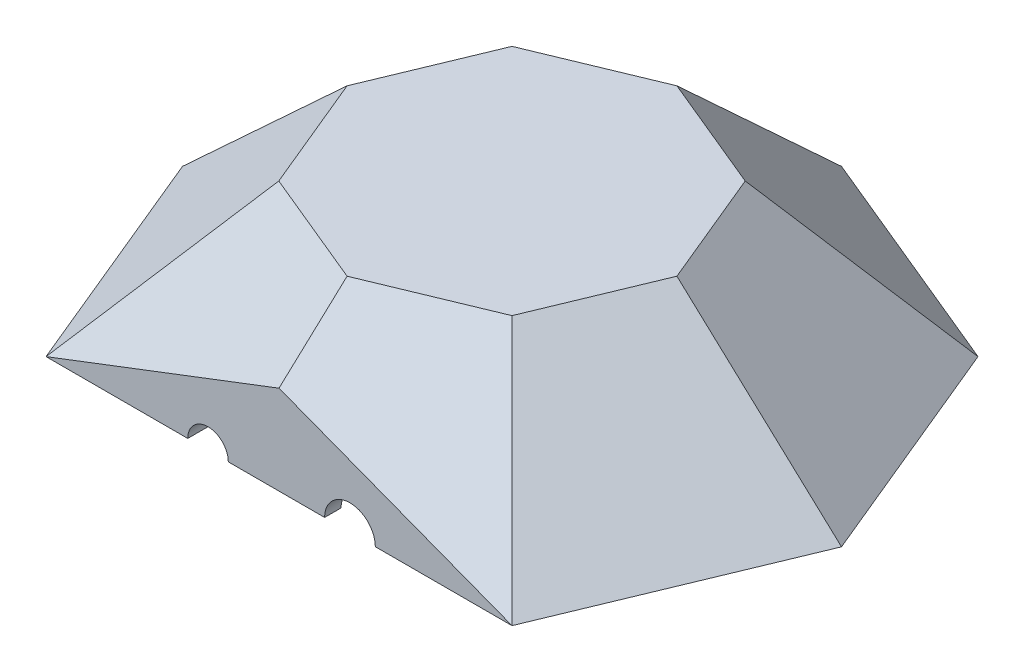
SolidWorks part; units mm, degrees
ref_plane "Ebene vorne" through (0, 0, 0) normal (0, 0, 1) x (1, 0, 0)
ref_plane "Ebene oben" through (0, 0, 0) normal (0, 1, 0) x (1, 0, 0)
ref_plane "Ebene rechts" through (0, 0, 0) normal (1, 0, 0) x (0, 0, -1)
sketch "Skizze1" plane through (0, 0, 0) normal (0, 1, 0) x (1, 0, 0)
  line L1 (-55, 0) -> (55, 0) construction
  line L5 (45.9619, -45.9619) -> (65, 0)
  line L6 (-65, 0) -> (65, 0) construction
  line L7 (0, -55) -> (0, 55) construction
  line L8 (0, 65) -> (0, -65) construction
  line L9 (0, -65) -> (45.9619, -45.9619)
  line L10 (45.9619, 45.9619) -> (-45.9619, -45.9619) construction
  line L11 (45.9619, -45.9619) -> (-45.9619, 45.9619) construction
  line L12 (-45.9619, -45.9619) -> (0, -65)
  line L15 (-65, 0) -> (-45.9619, -45.9619)
  line L16 (-45.9619, 45.9619) -> (-65, 0)
  line L19 (0, 65) -> (-45.9619, 45.9619)
  line L20 (45.9619, 45.9619) -> (0, 65)
  line L23 (65, 0) -> (45.9619, 45.9619)
  point P21 (0, 0)
  dimension "D1" = 45
  dimension "D2" = 130
  dimension "D5" = 4
extrude "Aufsatz-Linear austragen1" add sketch "Skizze1" along normal blind 30
ref_plane "Ebene1" through (26.8078, 0, 64.7198) normal (0.3827, 0, 0.9239) x (0.9239, 0, -0.3827)
ref_plane "Ebene3" through (-26.8078, 0, 64.7198) normal (-0.3827, 0, 0.9239) x (0.9239, 0, 0.3827)
ref_plane "Ebene4" through (-64.7198, 0, 26.8078) normal (-0.9239, 0, 0.3827) x (0.3827, 0, 0.9239)
ref_plane "Ebene5" through (-64.7198, 0, -26.8078) normal (-0.9239, 0, -0.3827) x (-0.3827, 0, 0.9239)
ref_plane "Ebene6" through (-26.8078, 0, -64.7198) normal (-0.3827, 0, -0.9239) x (-0.9239, 0, 0.3827)
sketch "Skizze6" plane through (-26.8078, 0, 64.7198) normal (-0.3827, 0, 0.9239) x (0.9239, 0, 0.3827)
  line L0 (-60.0522, 30) -> (-30.0522, 0)
  line L1 (-30.0522, 0) -> (-60.0522, 0)
  line L2 (71.5, 0) -> (-71.5, 0) construction
  line L3 (-60.0522, 0) -> (-60.0522, 30)
  line L4 (30.0522, 0) -> (60.0522, 30)
  line L5 (60.0522, 30) -> (60.0522, 0)
  line L6 (60.0522, 30) -> (60.0522, 0) construction
  line L7 (60.0522, 0) -> (30.0522, 0)
  dimension "D1" = 30
  dimension "D2" = 30
extrude "Schnitt-Linear austragen4" cut sketch "Skizze6" against normal through all
sketch "Skizze7" plane through (-64.7198, 0, 26.8078) normal (-0.9239, 0, 0.3827) x (0.3827, 0, 0.9239)
  line L0 (-60.0522, 30) -> (-30.0522, 0)
  line L1 (71.5, 0) -> (-71.5, 0) construction
  line L2 (-30.0522, 0) -> (-60.0522, 0)
  line L3 (-60.0522, 0) -> (-60.0522, 30) construction
  line L4 (-60.0522, 0) -> (-60.0522, 30)
  line L5 (30.0522, 0) -> (60.0522, 0)
  line L6 (24.8744, 0) -> (60.0522, 0) construction
  line L7 (60.0522, 30) -> (60.0522, 0) construction
  line L8 (60.0522, 0) -> (60.0522, 30)
  line L9 (60.0522, 30) -> (30.0522, 0)
  dimension "D1" = 30
  dimension "D2" = 30
extrude "Schnitt-Linear austragen5" cut sketch "Skizze7" against normal through all
sketch "Skizze8" plane through (-64.7198, 0, -26.8078) normal (-0.9239, 0, -0.3827) x (-0.3827, 0, 0.9239)
  line L0 (-60.0522, 30) -> (-60.0522, 0)
  line L1 (81.0088, 0) -> (-81.0088, 0) construction
  line L2 (-60.0522, 0) -> (-60.0522, 30) construction
  line L3 (-60.0522, 0) -> (-30.0522, 0)
  line L4 (-30.0522, 0) -> (-60.0522, 30)
  line L5 (60.0522, 30) -> (60.0522, 0)
  line L6 (60.0522, 0) -> (30.0522, 0)
  line L7 (54.8744, 0) -> (-12.448, 0) construction
  line L8 (30.0522, 0) -> (60.0522, 30)
  dimension "D1" = 30
  dimension "D2" = 30
extrude "Schnitt-Linear austragen6" cut sketch "Skizze8" against normal through all
sketch "Skizze9" plane through (-26.8078, 0, -64.7198) normal (-0.3827, 0, -0.9239) x (-0.9239, 0, 0.3827)
  line L0 (60.0522, 30) -> (60.0522, 0)
  line L1 (71.5, 0) -> (-71.5, 0) construction
  line L2 (60.0522, 0) -> (30.0522, 0)
  line L3 (30.0522, 0) -> (60.0522, 30)
  line L4 (-60.0522, 30) -> (-60.0522, 0)
  line L5 (-60.0522, 0) -> (-30.0522, 0)
  line L6 (-30.0522, 0) -> (-60.0522, 30)
  dimension "D1" = 30
  dimension "D2" = 30
extrude "Schnitt-Linear austragen7" cut sketch "Skizze9" against normal through all
shell "Wandung1" thickness 3
ref_plane "Ebene7" through (0, 0, 30) normal (0, 0, 1) x (1, 0, 0)
sketch "Skizze15" plane through (0, 0, 0) normal (1, 0, 0) x (0, 0, -1)
  line L0 (-45.9619, 30) -> (-45.9619, 12.4111)
  line L1 (-65, 30) -> (-32.5282, 0) construction
  line L2 (-45.9619, 12.4111) -> (-65, 30)
  line L3 (-65, 30) -> (-45.9619, 30)
extrude "Schnitt-Linear austragen12" cut sketch "Skizze15" against normal through all and the other way through all
ref_plane "Ebene9" through (0, 30, 0) normal (0, 1, 0) x (1, 0, 0)
sketch "Skizze17" plane through (0, 30, 0) normal (0, 1, 0) x (1, 0, 0)
  line L0 (34.8754, -45.9619) -> (45.9619, -45.9619) construction
  line L1 (-42.7148, -42.7148) -> (42.7148, -42.7148)
  line L2 (-42.7148, -42.7148) -> (-42.7148, -45.9619)
  line L3 (-42.7148, -45.9619) -> (42.7148, -45.9619)
  line L4 (42.7148, -42.7148) -> (42.7148, -45.9619)
extrude "Aufsatz-Linear austragen3" add sketch "Skizze17" against normal up to next
sketch "Skizze18" plane through (0, 0, 45.9619) normal (0, 0, 1) x (1, 0, 0)
  line L0 (-45.9619, 30) -> (45.9619, 30) construction
  line L1 (0, -16.5) -> (0, 16.5) construction
  circle A0 centre (-14, 30) radius 4
  circle A1 centre (14, 30) radius 5
  dimension "D1" = 10
  dimension "D2" = 8
  dimension "D3" = 14
  dimension "D4" = 14
extrude "Schnitt-Linear austragen14" cut sketch "Skizze18" against normal up to next
sketch "Skizze19" plane through (0, 0, 42.7148) normal (0, 0, -1) x (-1, 0, 0)
  line L0 (8, 30) -> (10, 30)
  line L1 (18, 30) -> (20, 30)
  line L2 (27.0468, 40.6883) -> (27.0466, 40.7453)
  arc A0 (10, 30) -> (18, 30) centre (14, 30) ccw
  arc A1 (8, 30) -> (20, 30) centre (14, 30) ccw
  circle A2 centre (14, 30) radius 6 construction
  circle A3 centre (14, 30) radius 4 construction
  arc M3 (18, 30) -> (10, 30) centre (14, 30) cw
  line M4 (10, 30) -> (-9, 30)
  line M9 (42.7148, 30) -> (18, 30)
  dimension "D1" = 2
extrude "Aufsatz-Linear austragen4" add sketch "Skizze19" along normal blind 0.75 contours A1 M4 M9 M3
sketch "Skizze20" plane through (0, 0, 42.7148) normal (0, 0, -1) x (-1, 0, 0)
  line L0 (8, 30) -> (5, 30)
  line L1 (-9, 30) -> (8, 30) construction
  line L2 (5, 30) -> (5, 23)
  line L3 (5, 23) -> (23, 23)
  line L4 (23, 23) -> (23, 30)
  line L5 (20, 30) -> (42.7148, 30) construction
  line L6 (23, 30) -> (20, 30)
  arc A0 (8, 30) -> (20, 30) centre (14, 30) ccw
  dimension "D2" = 3
  dimension "D3" = 3
  dimension "D4" = 7
extrude "Aufsatz-Linear austragen5" add sketch "Skizze20" along normal blind 2
sketch "Skizze23" plane through (0, 30, 0) normal (0, 1, 0) x (1, 0, 0)
  line L0 (-16.5, 0) -> (16.5, 0) construction
  line L1 (0, -16.5) -> (0, 16.5) construction
  circle A0 centre (-52.4078, 0) radius 5.3078
  circle A1 centre (52.4078, 0) radius 5
  circle A2 centre (0, 52.4078) radius 5
  dimension "D1" = 10
  dimension "D5" = 10
  dimension "D2" = 8
  dimension "D3" = 8
  dimension "D4" = 8
extrude "Aufsatz-Linear austragen9" add sketch "Skizze23" against normal up to body
ref_plane "Ebene10" through (0, 29.6, 0) normal (0, 1, 0) x (1, 0, 0)
sketch "Skizze25" plane through (0, 29.6, 0) normal (0, 1, 0) x (1, 0, 0)
  circle A0 centre (0, 52.4078) radius 3.2
  circle A1 centre (52.4078, 0) radius 3.2
  circle A2 centre (-52.4078, 0) radius 3.2
  dimension "D1" = 6.4
  dimension "D2" = 6.4
  dimension "D3" = 6.4
extrude "Schnitt-Linear austragen15" cut sketch "Skizze25" against normal blind 2.05
mirror "Spiegeln2" about plane through (0, 30, 0) normal (0, 1, 0) of bodies 126
sketch "Skizze26" plane through (0, 0, 0) normal (0, 0, 1) x (1, 0, 0)
  line L0 (61.0291, 30) -> (-61.0291, 30) construction
  line L1 (-65, 30) -> (64.9735, 30)
  line L2 (-65, 30) -> (-65, 0)
  line L3 (-65, 0) -> (64.9735, 0)
  line L4 (64.9735, 30) -> (64.9735, 0)
  line L5 (-32.5282, 0) -> (-65, 30) construction
  line L6 (61.0291, 0) -> (-61.0291, 0) construction
extrude "Schnitt-Linear austragen16" cut sketch "Skizze26" against normal through all and the other way through all
